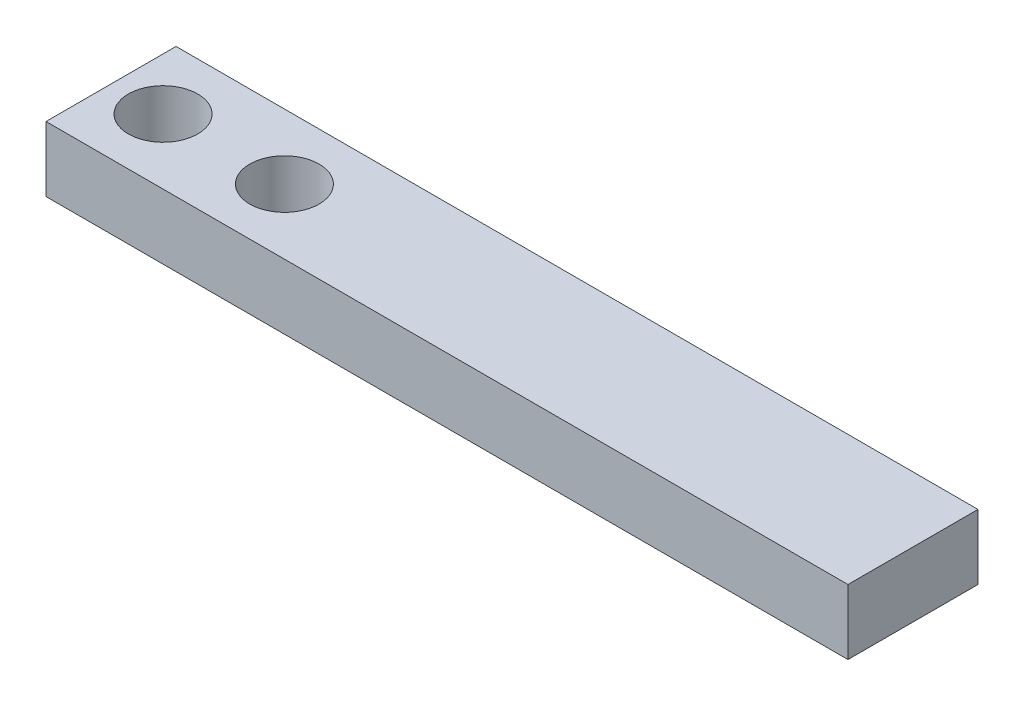
SolidWorks part; units mm, degrees
ref_plane "Front Plane" through (0, 0, 0) normal (0, 0, 1) x (1, 0, 0)
ref_plane "Top Plane" through (0, 0, 0) normal (0, 1, 0) x (1, 0, 0)
ref_plane "Right Plane" through (0, 0, 0) normal (1, 0, 0) x (0, 0, -1)
sketch "Sketch1" plane through (0, 0, 0) normal (0, 1, 0) x (1, 0, 0)
  line L1 (0, 0) -> (18.5, 0)
  line L2 (0, 0) -> (0, 3)
  line L3 (0, 3) -> (18.5, 3)
  line L4 (18.5, 0) -> (18.5, 3)
extrude "Boss-Extrude1" add sketch "Sketch1" along normal blind 1.5
hole_wizard "#97 (0.0059) Diameter Hole1" positions "Sketch3" profile "Sketch2" hole size "#97" standard "ANSI Inch" end condition through all
sketch "Sketch3" plane through (0, 1.5, 0) normal (0, 1, 0) x (1, 0, 0)
  line L0 (0, 3) -> (0, 0) construction
  point P0 (1.2, 1.5)
  point P2 (4, 1.5)
  dimension "D1" = 1.2
  dimension "D2" = 4
sketch "Sketch2" plane through (1.2, 1.5, -1.5) normal (1, 0, 0) x (0, 0, 1)
  line L0 (0, 0) -> (0, 1.5)
  line L1 (0, 1.5) -> (0.8, 1.5)
  line L2 (0.8, 1.5) -> (0.8, 0)
  line L5 (0.8, 0) -> (0, 0)
  line L11 (0, -6.35) -> (0, 107.95) construction
  dimension "Thru Hole Dia." = 1.6
  dimension "Thru Hole Depth" = 1.5
